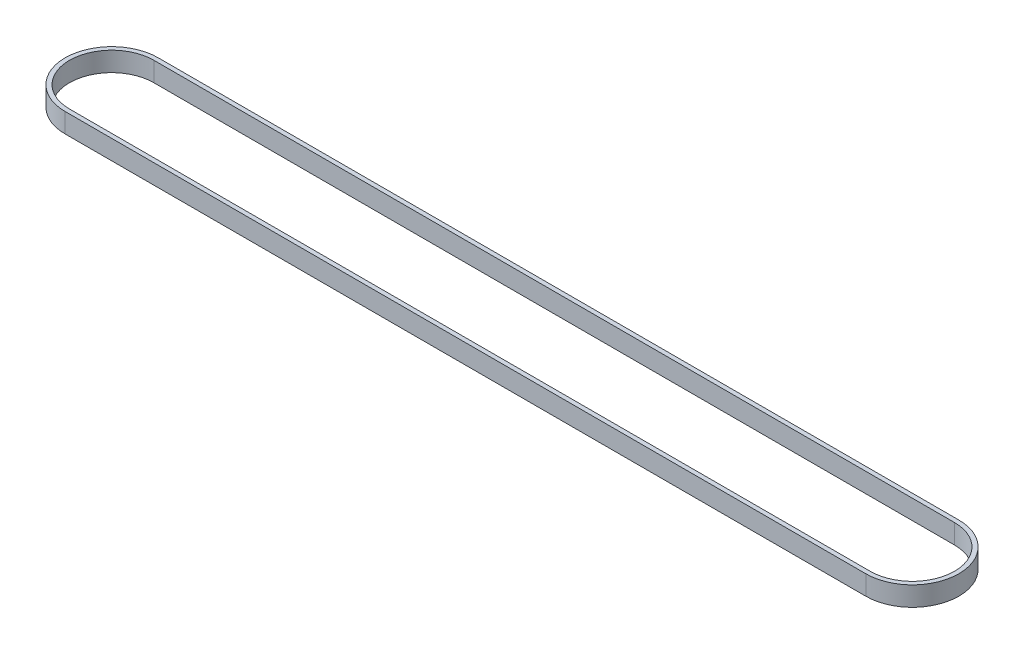
SolidWorks part; units mm, degrees
ref_plane "Piano frontale" through (0, 0, 0) normal (0, 0, 1) x (1, 0, 0)
ref_plane "Piano superiore" through (0, 0, 0) normal (0, 1, 0) x (1, 0, 0)
ref_plane "Piano destro" through (0, 0, 0) normal (1, 0, 0) x (0, 0, -1)
sketch "Schizzo1" plane through (0, 0, 0) normal (0, 1, 0) x (1, 0, 0)
  line L0 (-185, 0) -> (185, 0) construction
  line L1 (-185, 19.5) -> (185, 19.5)
  line L2 (-185, -19.5) -> (185, -19.5)
  line L3 (-185, 0) -> (185, 0) construction
  line L4 (-185, 21.5) -> (185, 21.5)
  line L5 (-185, -21.5) -> (185, -21.5)
  arc A0 (-185, 19.5) -> (-185, -19.5) centre (-185, 0) ccw
  arc A1 (185, -19.5) -> (185, 19.5) centre (185, 0) ccw
  arc A2 (-185, 21.5) -> (-185, -21.5) centre (-185, 0) ccw
  arc A3 (185, -21.5) -> (185, 21.5) centre (185, 0) ccw
  point P3 (0, 0)
  point P10 (0, 0)
  dimension "D3" = 19.5
  dimension "D1" = 370
  dimension "D2" = 2
extrude "Estrusione-Estrusione1" add sketch "Schizzo1" along normal mid plane 9
